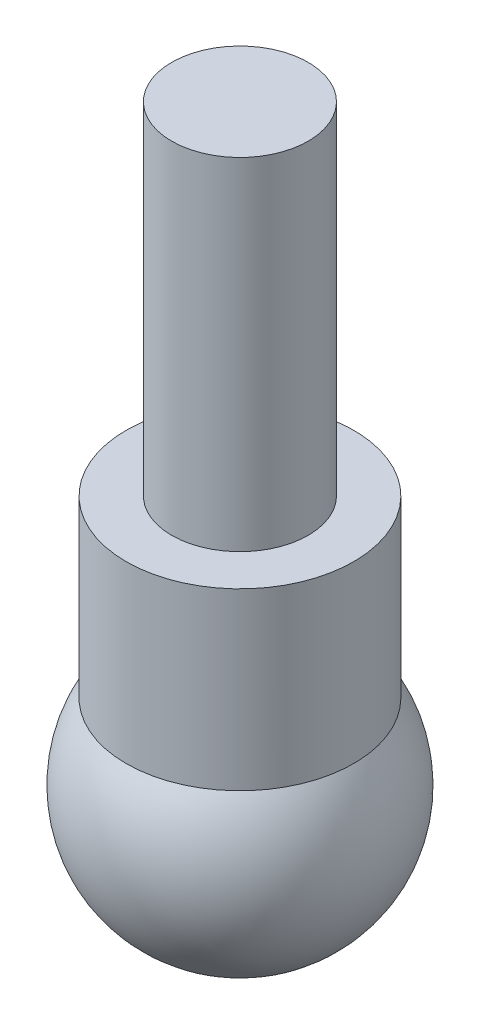
SolidWorks part; units mm, degrees
ref_plane "前视基准面" through (0, 0, 0) normal (0, 0, 1) x (1, 0, 0)
ref_plane "上视基准面" through (0, 0, 0) normal (0, 1, 0) x (1, 0, 0)
ref_plane "右视基准面" through (0, 0, 0) normal (1, 0, 0) x (0, 0, -1)
sketch "草图1" plane through (0, 0, 0) normal (0, 0, 1) x (1, 0, 0)
  line L0 (0, 26) -> (0, 0) construction
  line L1 (0, 26) -> (3, 26)
  line L2 (3, 26) -> (3, 11)
  line L3 (3, 11) -> (5, 11)
  line L4 (5, 11) -> (5, 3.3166)
  line L5 (0, 26) -> (0, 6)
  line L6 (0, 6) -> (0, -6)
  arc A0 (0, -6) -> (5, 3.3166) centre (0, 0) ccw
  dimension "D2" = 12
  dimension "D1" = 26
  dimension "D3" = 5
  dimension "D4" = 3
  dimension "D5" = 15
revolve "旋转1" add sketch "草图1" angle 360 about L0
